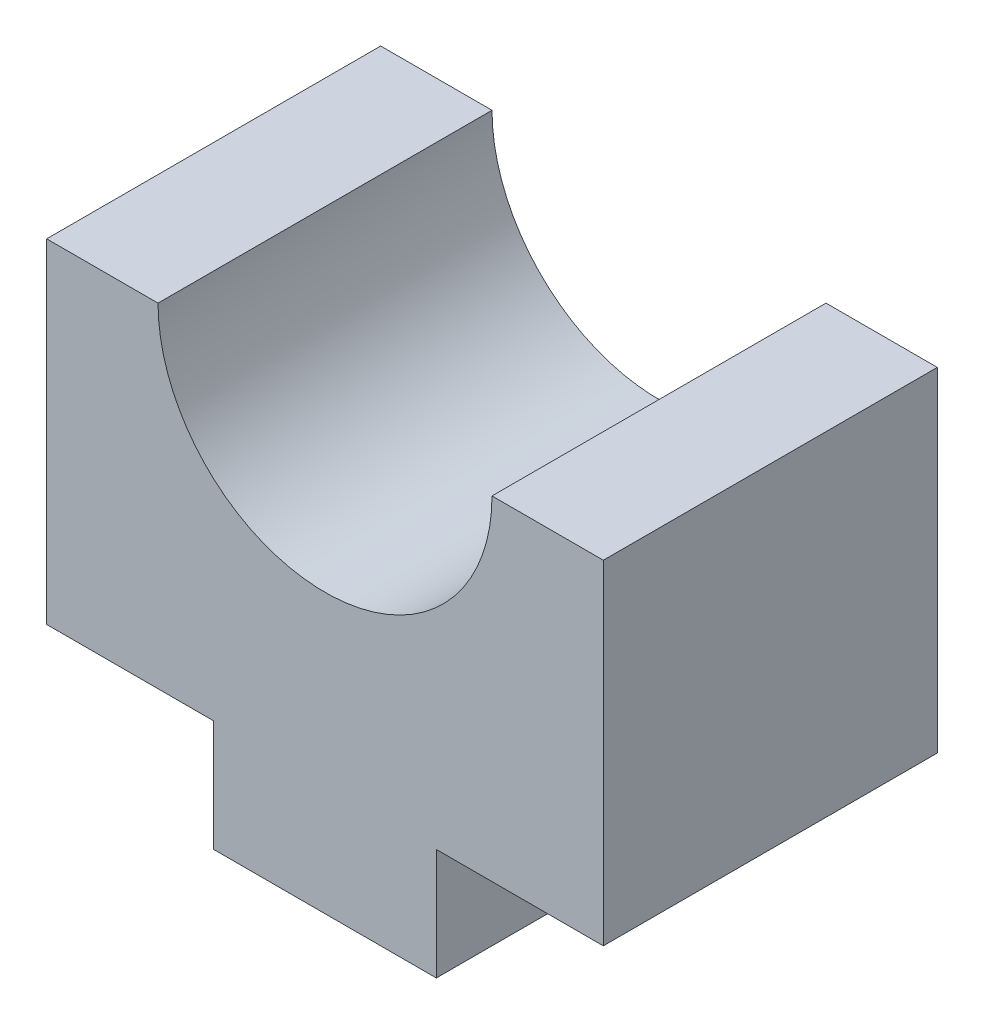
SolidWorks part; units mm, degrees
ref_plane "Alzado" through (0, 0, 0) normal (0, 0, 1) x (1, 0, 0)
ref_plane "Planta" through (0, 0, 0) normal (0, 1, 0) x (1, 0, 0)
ref_plane "Vista lateral" through (0, 0, 0) normal (1, 0, 0) x (0, 0, -1)
sketch "Croquis1" plane through (0, 0, 0) normal (0, 0, 1) x (1, 0, 0)
  line L0 (0, 0) -> (-10, 0)
  line L1 (-10, 0) -> (-10, 5)
  line L2 (-10, 5) -> (-17.5, 5)
  line L3 (-17.5, 5) -> (-17.5, 20)
  line L4 (-17.5, 20) -> (-12.5, 20)
  line L5 (2.5, 20) -> (7.5, 20)
  line L6 (7.5, 20) -> (7.5, 5)
  line L7 (7.5, 5) -> (0, 5)
  line L8 (0, 5) -> (0, 0)
  arc A0 (-12.5, 20) -> (2.5, 20) centre (-5, 20) ccw
  point P9 (-5, 0)
  dimension "D2" = 7.5
  dimension "D1" = 25
  dimension "D3" = 15
  dimension "D4" = 5
  dimension "D5" = 10
extrude "Saliente-Extruir1" add sketch "Croquis1" against normal blind 15
